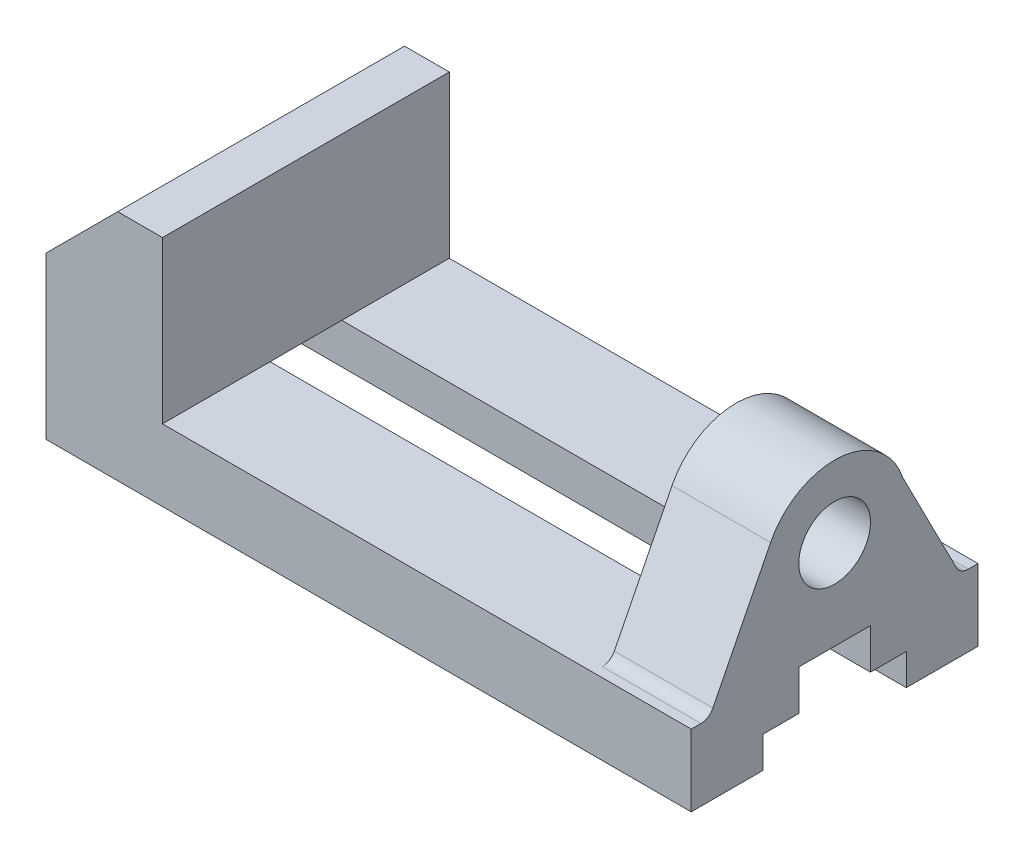
SolidWorks part; units mm, degrees
ref_plane "Front Plane" through (0, 0, 0) normal (0, 0, 1) x (1, 0, 0)
ref_plane "Top Plane" through (0, 0, 0) normal (0, 1, 0) x (1, 0, 0)
ref_plane "Right Plane" through (0, 0, 0) normal (1, 0, 0) x (0, 0, -1)
sketch "Sketch2" plane through (0, 0, 0) normal (0, 0, 1) x (1, 0, 0)
  line L1 (-72, 26) -> (72, 26)
  line L2 (-72, 26) -> (-72, -26)
  line L3 (-72, -26) -> (72, -26)
  line L4 (72, 26) -> (72, -26)
  line L5 (-72, 26) -> (72, -26) construction
  line L6 (-72, -26) -> (72, 26) construction
  point P0 (0, 0)
extrude "Boss-Extrude2" add sketch "Sketch2" along normal blind 64
sketch "Sketch3" plane through (0, 0, 64) normal (0, 0, 1) x (1, 0, 0)
  line L1 (72, 26) -> (-72, 26) construction
  line L3 (-46, 26) -> (-46, -10)
  line L4 (-46, -10) -> (50, -10)
  line L5 (50, -10) -> (50, 26)
  line L6 (-46, 26) -> (50, 26)
extrude "Cut-Extrude1" cut sketch "Sketch3" against normal blind 64
sketch "Sketch6" plane through (72, 0, 0) normal (1, 0, 0) x (0, 0, -1)
  line L0 (-64, -26) -> (-64, -10)
  line L1 (-64, -26) -> (-64, 26) construction
  line L2 (0, -26) -> (0, -10)
  line L4 (0, -26) -> (0, 26) construction
  line L7 (-64, -10) -> (-60, -10)
  line L8 (0, -10) -> (-4, -10)
  line L9 (-60, -10) -> (-46.2873, 17.2023)
  line L10 (-46.2873, 17.2023) -> (-41.8524, 26)
  line L11 (-64, 26) -> (0, 26) construction
  line L12 (-4, -10) -> (-19.0032, 19.3318)
  line L13 (-19.0032, 19.3318) -> (-22.414, 26)
  line L14 (-41.8524, 26) -> (-32, 26)
  line L15 (-32, 26) -> (-22.414, 26)
  line L16 (-41.8524, 26) -> (-64, 26)
  line L17 (-64, 26) -> (-64, -10)
  line L18 (0, 26) -> (0, -10)
  circle A0 centre (-32, 10) radius 16
  circle A1 centre (-32, 10) radius 8
  line M4 (0, -26) -> (0, 26)
  line M5 (0, 26) -> (-64, 26)
  line M6 (-64, 26) -> (-64, -26)
extrude "Cut-Extrude5" cut sketch "Sketch6" against normal blind 64 contours L9 L10 L7 M5 M6 | A0 L12 L8 L13 M4 M5 | A0 L13 M5 | A0 L10 M5 | A1
sketch "Sketch7" plane through (72, 0, 0) normal (1, 0, 0) x (0, 0, -1)
  line L0 (-64, -26) -> (0, -26) construction
  line L5 (-48, -26) -> (-16, -26)
  line L7 (-16, -26) -> (-16, -19)
  line L8 (-16, -19) -> (-48, -19)
  line L9 (-48, -26) -> (-48, -19)
  line L10 (-32, -26) -> (-48, -19) construction
  line L11 (-16, -19) -> (-32, -26) construction
  line L12 (-32, -19) -> (-40, -19)
  line L13 (-32, -19) -> (-24, -19)
  line L16 (-24, -19) -> (-24, -10)
  line L18 (-24, -10) -> (-40, -10)
  line L19 (-40, -10) -> (-40, -19)
  point P1 (-32, -26)
  point P3 (-40, -19)
  line M21 (-64, -26) -> (0, -26)
extrude "Cut-Extrude7" cut sketch "Sketch7" against normal through all contours L18 L19 L8 L16 | L9 L7 L8 M21
sketch "Sketch8" plane through (0, 0, 64) normal (0, 0, 1) x (1, 0, 0)
  line L0 (-72, 26) -> (-56, 26)
  line L1 (-46, 26) -> (-72, 26) construction
  line L2 (-72, 26) -> (-72, 10)
  line L3 (-72, 26) -> (-72, -26) construction
  line L4 (-72, 10) -> (-56, 26)
extrude "Cut-Extrude8" cut sketch "Sketch8" against normal through all
fillet "Fillet1" radius 3 2 edges at (61, -10, 4) (61, -10, 60)
sketch "Sketch10" plane through (0, -26, 0) normal (0, -1, 0) x (1, 0, 0)
  line L4 (-72, 64) -> (-36, 64)
  line L5 (-72, 64) -> (72, 64) construction
  line L13 (72, 64) -> (34, 64)
  line L15 (-72, 56) -> (-58.1915, 56) construction
  line L16 (-72, 64) -> (-72, 48) construction
  line L17 (-36, 56) -> (34, 56)
sketch "Sketch12" plane through (0, -26, 0) normal (0, -1, 0) x (1, 0, 0)
  line L0 (-72, 64) -> (-36, 64)
  line L1 (-72, 64) -> (72, 64) construction
  line L2 (-36, 64) -> (-36, 0)
  line L3 (-72, 0) -> (72, 0) construction
sketch "Sketch15" plane through (72, 0, 0) normal (1, 0, 0) x (0, 0, -1)
  point P1 (-59.1684, -8.3504)
  point P2 (-4.8357, -8.3662)
hole_wizard "Ø1.0mm Dowel Hole1" positions "3DSketch1" profile "Sketch17" hole size "Ø1.0" standard "ISO"
sketch3d "3DSketch1"
  line L1 (-72, -26, 56) -> (72, -26, 56)
  line L2 (-72, -26, 64) -> (-72, -26, 48) construction
  line L3 (72, -26, 64) -> (72, -26, 48) construction
  point P0 (-36, -26, 56)
  point P2 (34, -26, 56)
  dimension "D1" = 70
  dimension "D2" = 38
sketch "Sketch17" plane through (-36, -26, 56) normal (1, 0, 0) x (0, 0, -1)
  line L0 (0, 0) -> (0, 11.7321)
  line L1 (0, 11.7321) -> (3, 10)
  line L2 (3, 10) -> (3, 0)
  line L5 (3, 0) -> (0, 0)
  line L10 (0, 11.7321) -> (-3, 10) construction
  line L11 (0, -6.35) -> (0, 107.95) construction
  dimension "Hole Dia." = 6
  dimension "Hole Depth" = 10
  dimension "Drill Angle" = 120
hole_wizard "Ø1.0mm Dowel Hole2" positions "3DSketch2" profile "Sketch18" hole size "Ø1.0" standard "ISO"
sketch3d "3DSketch2"
  line L0 (-72, -26, 8) -> (72, -26, 8)
  line L1 (-72, -26, 16) -> (-72, -26, 0) construction
  line L2 (72, -26, 16) -> (72, -26, 0) construction
  point P0 (-36, -26, 8)
  point P2 (34, -26, 8)
  dimension "D1" = 70
  dimension "D2" = 38
sketch "Sketch18" plane through (-36, -26, 8) normal (1, 0, 0) x (0, 0, -1)
  line L0 (0, 0) -> (0, 11.7321)
  line L1 (0, 11.7321) -> (3, 10)
  line L2 (3, 10) -> (3, 0)
  line L5 (3, 0) -> (0, 0)
  line L10 (0, 11.7321) -> (-3, 10) construction
  line L11 (0, -6.35) -> (0, 107.95) construction
  dimension "Hole Dia." = 6
  dimension "Hole Depth" = 10
  dimension "Drill Angle" = 120
